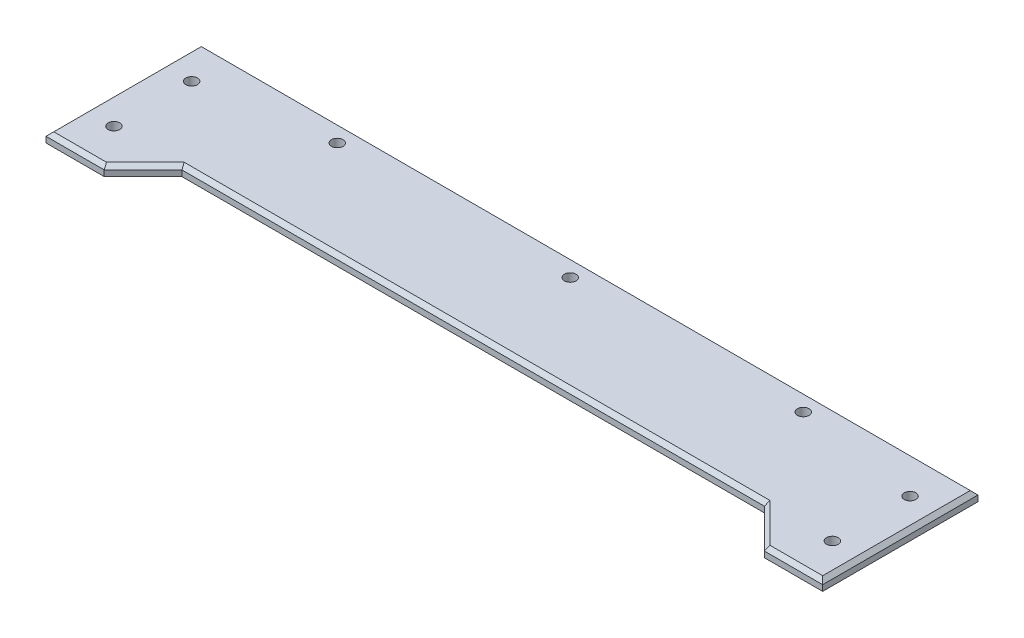
SolidWorks part; units mm, degrees
ref_plane "Alzado" through (0, 0, 0) normal (0, 0, 1) x (1, 0, 0)
ref_plane "Planta" through (0, 0, 0) normal (0, 1, 0) x (1, 0, 0)
ref_plane "Vista lateral" through (0, 0, 0) normal (1, 0, 0) x (0, 0, -1)
sketch "Croquis1" plane through (0, 0, 0) normal (0, 1, 0) x (1, 0, 0)
  line L0 (-149.6078, -39.6078) -> (-129.6078, -19.6078)
  line L1 (-179.6078, 40.3922) -> (220.3922, 40.3922)
  line L2 (-179.6078, 40.3922) -> (-179.6078, -39.6078)
  line L3 (-179.6078, -39.6078) -> (-149.6078, -39.6078)
  line L4 (220.3922, 40.3922) -> (220.3922, -39.6078)
  line L5 (-129.6078, -19.6078) -> (170.3922, -19.6078)
  line L6 (170.3922, -19.6078) -> (190.3922, -39.6078)
  line L7 (190.3922, -39.6078) -> (220.3922, -39.6078)
  circle A0 centre (-164.6078, 20.3922) radius 3
  circle A1 centre (-99.6078, 30.3922) radius 3
  circle A2 centre (140.3922, 30.3922) radius 3
  circle A3 centre (20.3922, 30.3922) radius 3
  circle A4 centre (-164.6078, -19.6078) radius 3
  circle A5 centre (205.3922, 20.3922) radius 3
  circle A6 centre (205.3922, -19.6078) radius 3
  dimension "D3" = 6
  dimension "D4" = 6
  dimension "D5" = 6
  dimension "D6" = 6
  dimension "D7" = 6
  dimension "D8" = 6
  dimension "D9" = 6
  dimension "D1" = 80
  dimension "D2" = 400
  dimension "D10" = 15
  dimension "D11" = 10
  dimension "D12" = 200
  dimension "D13" = 80
  dimension "D14" = 80
  dimension "D15" = 15
  dimension "D16" = 20
  dimension "D17" = 20
  dimension "D18" = 30
  dimension "D19" = 30
  dimension "D20" = 45
  dimension "D21" = 45
extrude "Saliente-Extruir1" add sketch "Croquis1" along normal blind 5
chamfer "Chaflán1" distance 2 angle 45 8 edges at (220.3922, 5, -0.3922) (20.3922, 5, -40.3922) (-179.6078, 5, -0.3922) (-164.6078, 5, 39.6078) (180.3922, 5, 29.6078) (205.3922, 5, 39.6078) (20.3922, 5, 19.6078) (-139.6078, 5, 29.6078)
